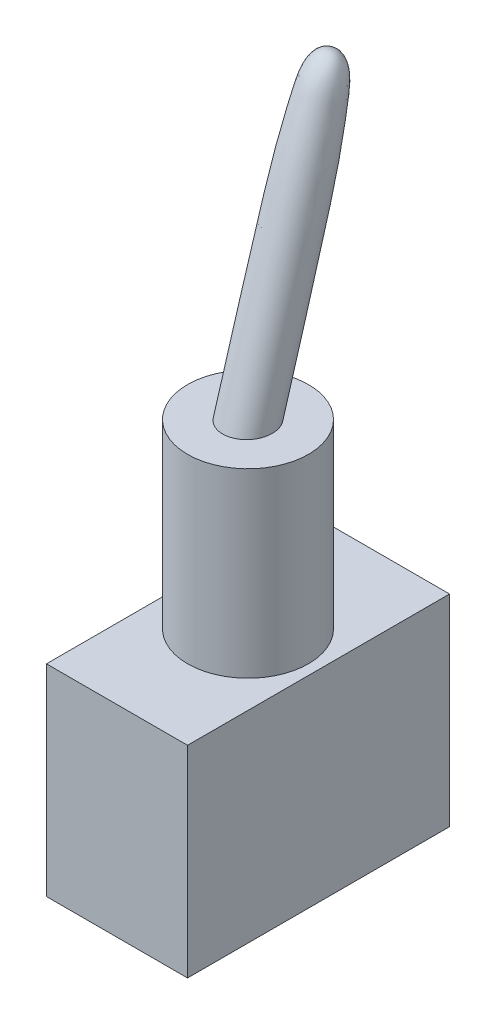
SolidWorks part; units mm, degrees
ref_plane "Piano frontale" through (0, 0, 0) normal (0, 0, 1) x (1, 0, 0)
ref_plane "Piano superiore" through (0, 0, 0) normal (0, 1, 0) x (1, 0, 0)
ref_plane "Piano destro" through (0, 0, 0) normal (1, 0, 0) x (0, 0, -1)
sketch "Schizzo1" plane through (0, 0, 0) normal (0, 1, 0) x (1, 0, 0)
  line L1 (0, 0) -> (7, 0)
  line L2 (0, 0) -> (0, 13)
  line L3 (0, 13) -> (7, 13)
  line L4 (7, 0) -> (7, 13)
  dimension "D1" = 13
  dimension "D2" = 7
extrude "Estrusione-Estrusione1" add sketch "Schizzo1" along normal blind 10
sketch "Schizzo2" plane through (0, 10, 0) normal (0, 1, 0) x (1, 0, 0)
  line L0 (7, 13) -> (0, 13) construction
  line L1 (7, 0) -> (7, 13) construction
  circle A0 centre (3.5, 6.5) radius 3
  dimension "D2" = 3.5
  dimension "D3" = 6
  dimension "D1" = 6.5
extrude "Estrusione-Estrusione2" add sketch "Schizzo2" along normal blind 9
ref_plane "Piano1" through (3.5, 0, 0) normal (1, 0, 0) x (0, 0, -1)
sketch "Schizzo5" plane through (3.5, 0, 0) normal (1, 0, 0) x (0, 0, -1)
  line L0 (6.5, 19) -> (10.6048, 32.9058)
  line L1 (9.5, 19) -> (3.5, 19) construction
  line L2 (6.1328, 13.5068) -> (10.3997, 27.9617) construction
  line L3 (12.8251, 32.2504) -> (10.8146, 32.8438) construction
  line L5 (7.444, 17.9487) -> (6.5, 19)
  spline S0 degree 3 poles (10.6048, 32.9058) (11.0662, 32.7696) (11.2795, 31.9326) (10.4385, 28.1124) (10.4285, 28.0594) (7.444, 17.9487) knots 0 0 0 0 0.119715 0.219715 1 1 1 1
  point P8 (0, 0)
  point P9 (12.4333, 31.1933)
  point P10 (0, 0)
  point P13 (7.444, 17.9487)
  point P14 (0, 0)
  point P15 (10.6048, 32.9058)
  point P16 (0, 0)
  point P17 (11.1757, 31.7046)
revolve "Rivoluzione1" add sketch "Schizzo5" angle 360 about L0
